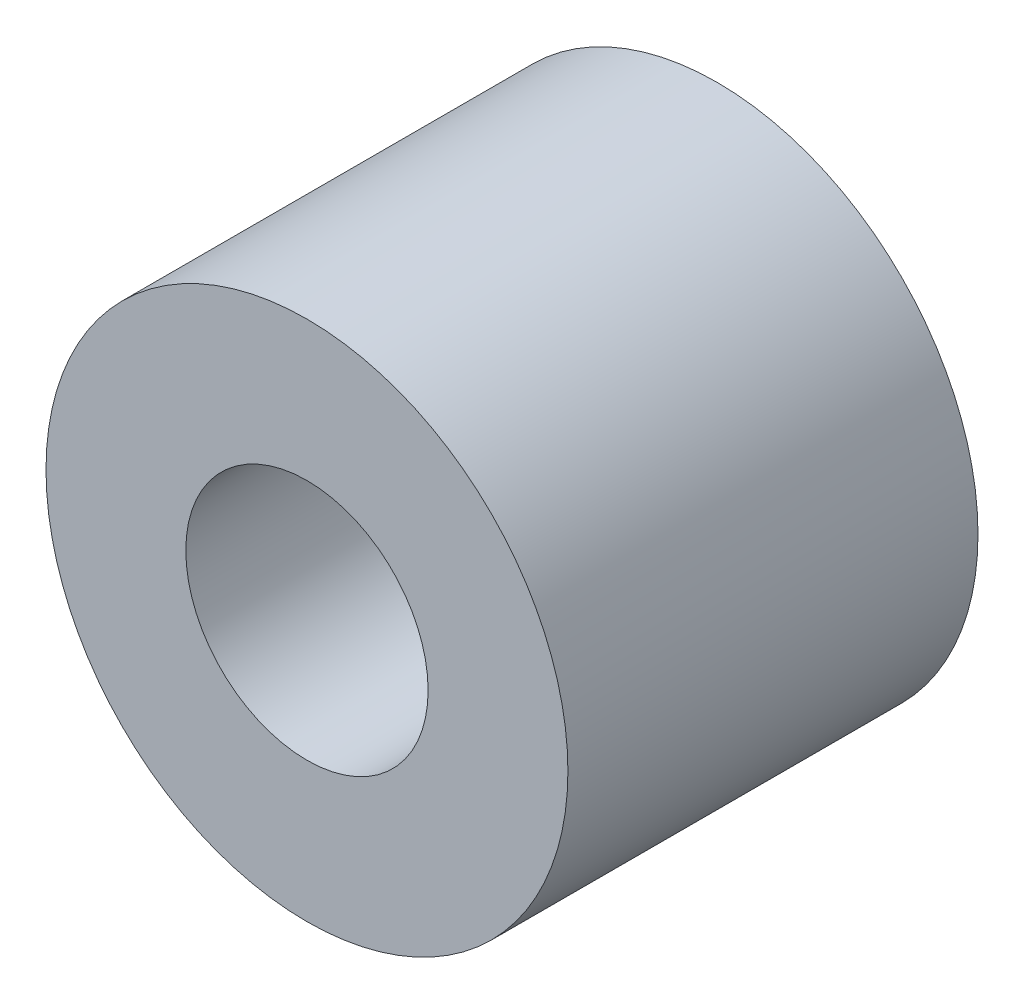
SolidWorks part; units mm, degrees
ref_plane "Plan de face" through (0, 0, 0) normal (0, 0, 1) x (1, 0, 0)
ref_plane "Plan de dessus" through (0, 0, 0) normal (0, 1, 0) x (1, 0, 0)
ref_plane "Plan de droite" through (0, 0, 0) normal (1, 0, 0) x (0, 0, -1)
sketch "Esquisse1" plane through (0, 0, 0) normal (0, 0, 1) x (1, 0, 0)
  line L1 (-0.9885, -3.25) -> (1.037, -3.25) construction
  circle A0 centre (0, 0) radius 7
  circle A1 centre (0, 0) radius 3.25
  point P3 (2.2747, 2.3213)
  dimension "D1" = 14
  dimension "D2" = 6.5
extrude "Boss.-Extru.1" add sketch "Esquisse1" along normal blind 11
